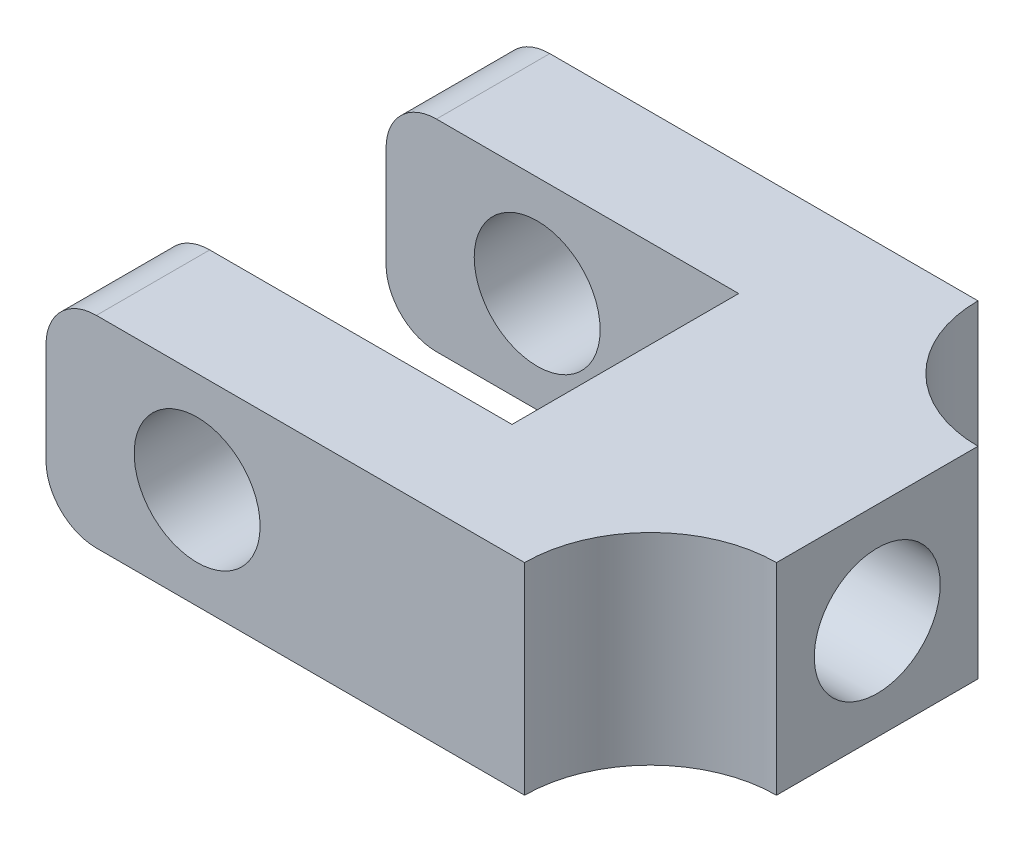
SolidWorks part; units mm, degrees
ref_plane "Front Plane" through (0, 0, 0) normal (0, 0, 1) x (1, 0, 0)
ref_plane "Top Plane" through (0, 0, 0) normal (0, 1, 0) x (1, 0, 0)
ref_plane "Right Plane" through (0, 0, 0) normal (1, 0, 0) x (0, 0, -1)
sketch "Sketch2" plane through (0, 0, 0) normal (0, 1, 0) x (1, 0, 0)
  line L0 (0, 4.5) -> (-14, 4.5)
  line L1 (-14, 4.5) -> (-14, 9)
  line L2 (-14, 9) -> (5, 9)
  line L3 (10, 4) -> (10, -4)
  line L4 (10, 0) -> (0, 0) construction
  line L5 (0, -4.5) -> (0, 4.5)
  line L6 (5, 18.5625) -> (5, -10.3807) construction
  line L7 (10, -10.3807) -> (10, 18.5625) construction
  line L8 (0, 0) -> (-35.1149, 0) construction
  line L9 (-14, -9) -> (5, -9)
  line L10 (-14, -4.5) -> (-14, -9)
  line L11 (0, -4.5) -> (-14, -4.5)
  arc A0 (5, 9) -> (10, 4) centre (10, 9) ccw
  arc A1 (5, -9) -> (10, -4) centre (10, -9) cw
  dimension "D2" = 5
  dimension "D1" = 4.5
  dimension "D3" = 4.5
  dimension "D4" = 14
  dimension "D5" = 10
extrude "Boss-Extrude1" add sketch "Sketch2" along normal mid plane 8
sketch "Sketch3" plane through (10, 0, 0) normal (1, 0, 0) x (0, 0, -1)
  circle A0 centre (0, 0) radius 2.5
  dimension "D1" = 5
extrude "Cut-Extrude1" cut sketch "Sketch3" against normal through all
sketch "Sketch4" plane through (0, 0, 0) normal (0, 0, 1) x (1, 0, 0)
  line L0 (-14, 4) -> (-14, -4) construction
  circle A0 centre (-8, 0) radius 2.5
  point P4 (0, 0)
  dimension "D1" = 5
  dimension "D2" = 6
extrude "Cut-Extrude2" cut sketch "Sketch4" against normal through all both and the other way through all
fillet "Fillet1" radius 2 4 edges at (-14, -4, -6.75) (-14, 4, -6.75) (-14, -4, 6.75) (-14, 4, 6.75)
